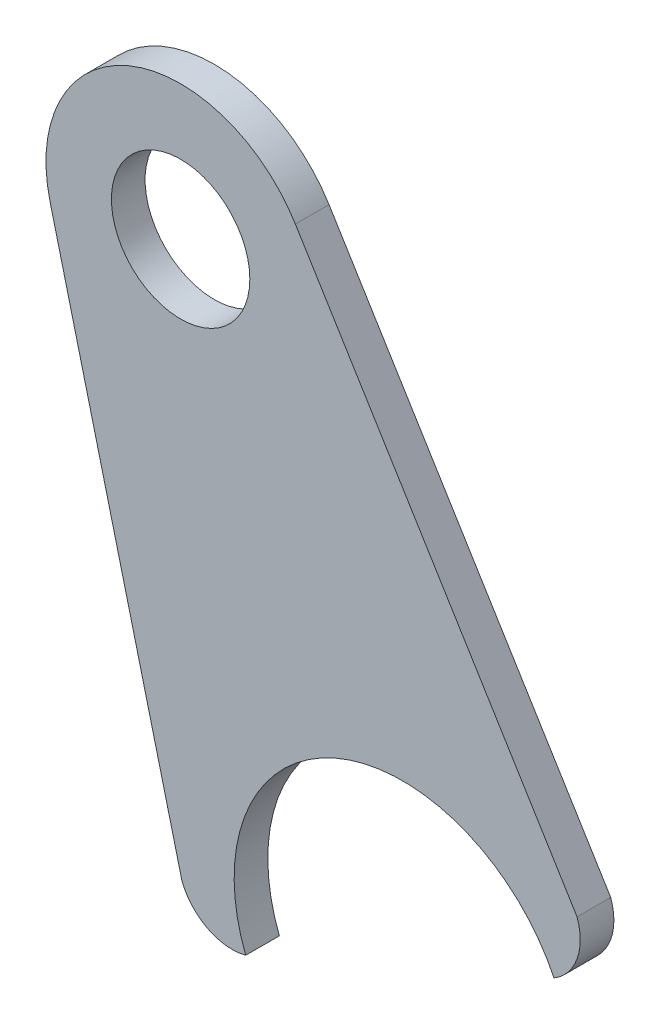
SolidWorks part; units mm, degrees
ref_plane "Front Plane" through (0, 0, 0) normal (0, 0, 1) x (1, 0, 0)
ref_plane "Top Plane" through (0, 0, 0) normal (0, 1, 0) x (1, 0, 0)
ref_plane "Right Plane" through (0, 0, 0) normal (1, 0, 0) x (0, 0, -1)
sketch "Sketch1" plane through (0, 0, 0) normal (0, 0, 1) x (1, 0, 0)
  line L5 (7.1468, 3.4535) -> (-7.3933, -2.8886) construction
  line L8 (-10.3992, -1.3553) -> (-16.6189, 23.2714)
  line L9 (8.2327, 6.4965) -> (-5.0496, 28.1469)
  arc A2 (7.1468, 3.4535) -> (8.2327, 6.4965) centre (5.8437, 5.6337) ccw
  arc A3 (7.1468, 3.4535) -> (-7.3933, -2.8886) centre (0, 0) ccw
  arc A4 (-16.6189, 23.2714) -> (-5.0496, 28.1469) centre (-10.4622, 24.8263) cw
  arc A5 (-7.3933, -2.8886) -> (-10.3992, -1.3553) centre (-8.0335, -0.4306) cw
  circle A6 centre (-10.4622, 24.8263) radius 3.2639
  dimension "D1" = 6.35
  dimension "D2" = 15.875
  dimension "D3" = 2.54
  dimension "D4" = 2.54
  dimension "D7" = 6.5278
  dimension "D5" = 25.4
  dimension "D6" = 25.4
extrude "Boss-Extrude1" add sketch "Sketch1" along normal blind 1.5875
ref_point "Point3"
